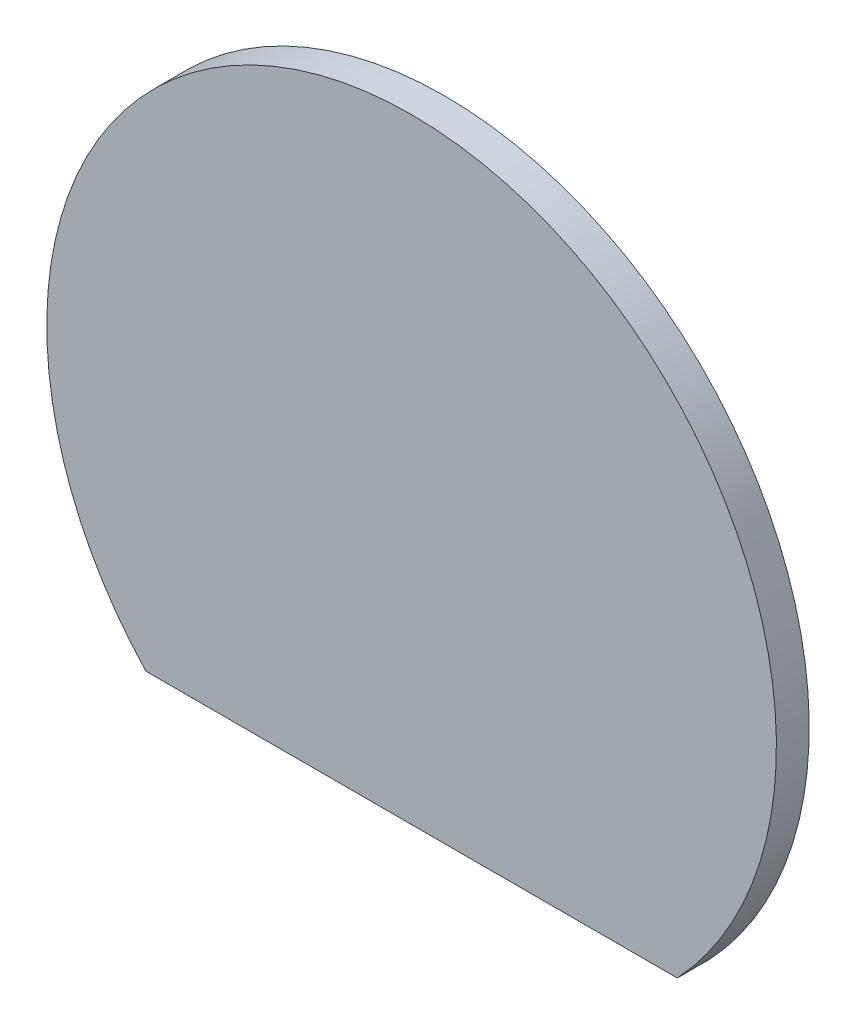
SolidWorks part; units mm, degrees
ref_plane "Plan de face" through (0, 0, 0) normal (0, 0, 1) x (1, 0, 0)
ref_plane "Plan de dessus" through (0, 0, 0) normal (0, 1, 0) x (1, 0, 0)
ref_plane "Plan de droite" through (0, 0, 0) normal (1, 0, 0) x (0, 0, -1)
sketch "Contour" plane through (0, 0, 0) normal (0, 0, 1) x (1, 0, 0)
  line L0 (0, 17.8) -> (0, -12.2) construction
  line L1 (0, -0.88) -> (0, 0.88) construction
  line L2 (-12.9615, -12.2) -> (12.9615, -12.2)
  arc A0 (12.9615, -12.2) -> (-12.9615, -12.2) centre (0, 0) ccw
  dimension "D1" = 35.6
  dimension "D2" = 30
extrude "Boss.-Extru.1_Contour" add sketch "Contour" along normal blind 1.6
